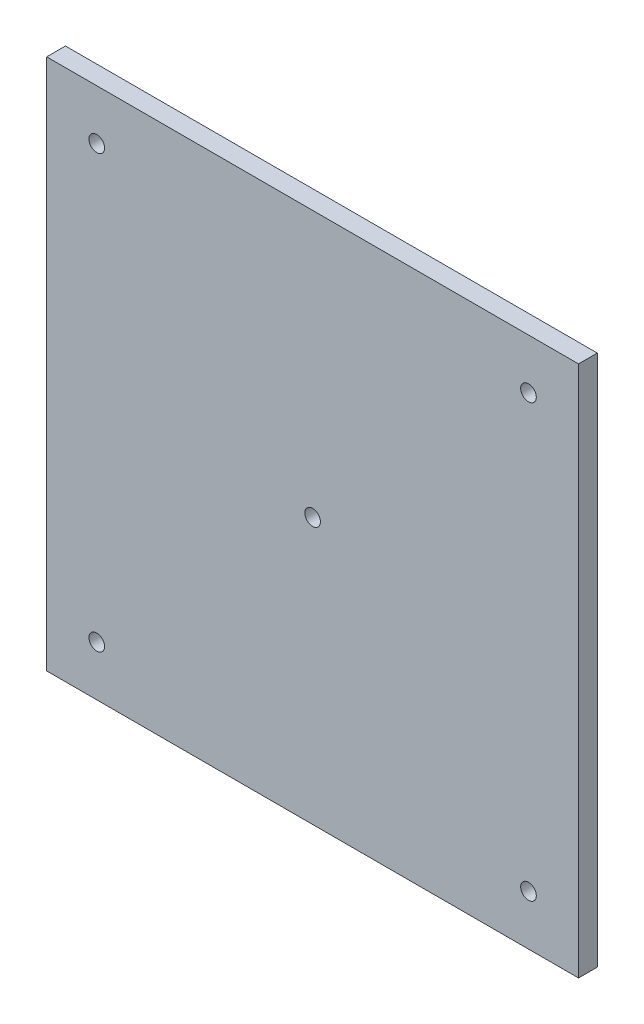
SolidWorks part; units mm, degrees
ref_plane "Plan de face" through (0, 0, 0) normal (0, 0, 1) x (1, 0, 0)
ref_plane "Plan de dessus" through (0, 0, 0) normal (0, 1, 0) x (1, 0, 0)
ref_plane "Plan de droite" through (0, 0, 0) normal (1, 0, 0) x (0, 0, -1)
sketch "Esquisse1" plane through (0, 0, 0) normal (0, 0, 1) x (1, 0, 0)
  line L1 (-32.6125, 19.2) -> (52.3875, 19.2)
  line L2 (-32.6125, 19.2) -> (-32.6125, -65.8)
  line L3 (-32.6125, -65.8) -> (52.3875, -65.8)
  line L4 (52.3875, 19.2) -> (52.3875, -65.8)
  dimension "D1" = 85
  dimension "D2" = 85
extrude "Boss.-Extru.1" add sketch "Esquisse1" along normal blind 3
sketch "Esquisse2" plane through (0, 0, 3) normal (0, 0, 1) x (1, 0, 0)
  line L0 (-32.6125, 19.2) -> (-32.6125, -65.8) construction
  line L1 (52.3875, 19.2) -> (-32.6125, 19.2) construction
  line L2 (52.3875, -65.8) -> (52.3875, 19.2) construction
  line L3 (-32.6125, -65.8) -> (52.3875, -65.8) construction
  circle A0 centre (-24.6125, 11.2) radius 1.25
  circle A1 centre (44.3875, 11.2) radius 1.25
  circle A2 centre (-24.6125, -57.8) radius 1.25
  circle A3 centre (44.3875, -57.8) radius 1.25
  dimension "D1" = 2.5
  dimension "D4" = 2.5
  dimension "D5" = 2.5
  dimension "D9" = 2.5
  dimension "D2" = 8
  dimension "D3" = 8
  dimension "D6" = 8
  dimension "D7" = 8
  dimension "D8" = 8
  dimension "D10" = 97.5807
extrude "Enlèv. mat.-Extru.1" cut sketch "Esquisse2" against normal blind 3
sketch "Esquisse3" plane through (0, 0, 3) normal (0, 0, 1) x (1, 0, 0)
  line L0 (-32.6125, 19.2) -> (-32.6125, -65.8) construction
  line L2 (52.3875, 19.2) -> (-32.6125, 19.2) construction
  circle A0 centre (9.8875, -23.3) radius 1.25
  dimension "D3" = 2.5
  dimension "D1" = 42.5
  dimension "D2" = 42.5
extrude "Enlèv. mat.-Extru.2" cut sketch "Esquisse3" against normal blind 10
